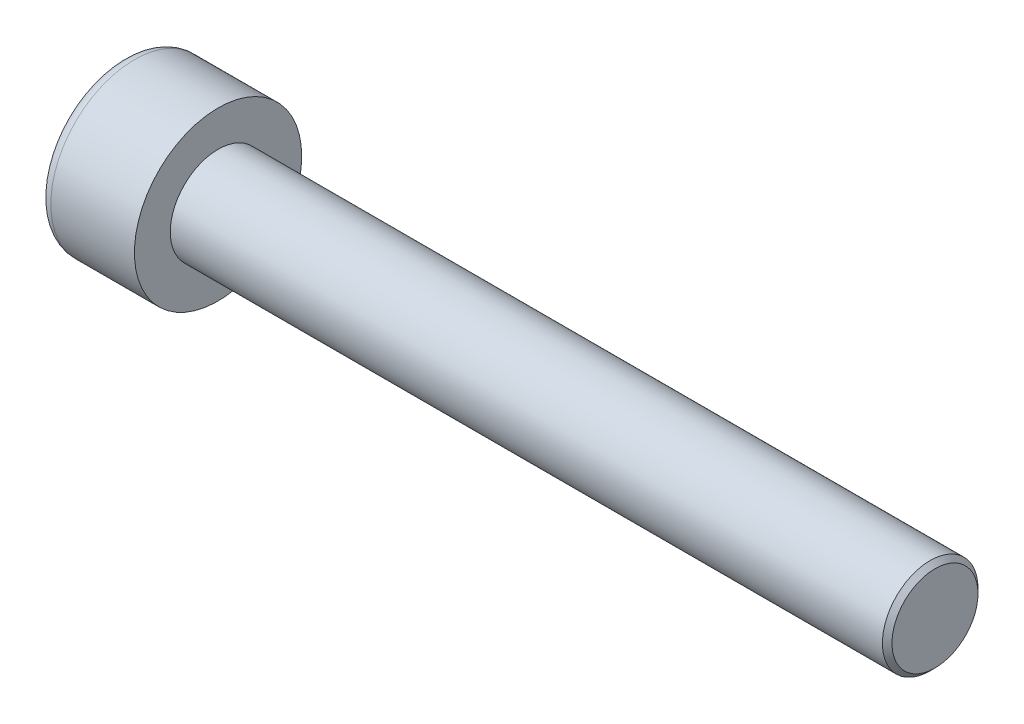
SolidWorks part; units mm, degrees
ref_plane "Front" through (0, 0, 0) normal (0, 0, 1) x (1, 0, 0)
ref_plane "Top" through (0, 0, 0) normal (0, 1, 0) x (1, 0, 0)
ref_plane "Right" through (0, 0, 0) normal (1, 0, 0) x (0, 0, -1)
other "Configuration Table"
sketch "Sketch1" plane through (0, 0, 0) normal (1, 0, 0) x (0, 0, -1)
  circle A0 centre (0, 0) radius 3.5
  dimension "dk" = 7
extrude "BaseHead" add sketch "Sketch1" along normal blind 4
sketch "Sketch2" plane through (4, 0, 0) normal (1, 0, 0) x (0, 0, -1)
  circle A0 centre (0, 0) radius 2
  dimension "d" = 4
extrude "BaseBody" add sketch "Sketch2" along normal blind 30
cosmetic thread "ThreadCosmetic1" [suppressed] parameters "b"=20, "D2"=3.242
sketch "Sketch3" plane through (0, 0, 0) normal (1, 0, 0) x (0, 0, -1)
  line L1 (1.7321, 0) -> (0.866, 1.5)
  line L2 (0.866, 1.5) -> (-0.866, 1.5)
  line L3 (-0.866, 1.5) -> (-1.7321, 0)
  line L4 (-1.7321, 0) -> (-0.866, -1.5)
  line L5 (-0.866, -1.5) -> (0.866, -1.5)
  line L6 (0.866, -1.5) -> (1.7321, 0)
  circle A0 centre (0, 0) radius 1.5 construction
  dimension "s" = 3
  dimension "e" = 3.4641
extrude "HexagonSocket" cut sketch "Sketch3" along normal blind 2
sketch "Sketch4" plane through (-4.1961, 0.75, 0) normal (0, 0, 1) x (-1, 0, 0)
  line L0 (-6.1961, 2.25) -> (-7.0622, 0.75)
  line L2 (-7.0622, 0.75) -> (-6.1961, 0.75)
  line L3 (-6.1961, 0.75) -> (-6.1961, 2.25)
  line L4 (-5.0351, 0.75) -> (0.839, 0.75) construction
  line L5 (-38.1961, 0.75) -> (-8.1961, 0.75) construction
  line L6 (-8.1961, 0.75) -> (-4.1961, 0.75) construction
  dimension "m" = 60
revolve "Cut-Revolve1" cut sketch "Sketch4" angle 360 about L4
fillet "HeadFillet" [suppressed] radius 0.2
fillet "TopFillet" radius 0.5 1 edges at (0, 0, -3.5)
chamfer "Chamfer1" distance 0.2 angle 45 1 edges at (34, 0, -2)
sketch "Sketch5" plane through (0, 0, 0) normal (0, 0, 1) x (1, 0, 0)
  line L0 (33.8, 1.6718) -> (33.9895, 2)
  line L1 (33.9895, 2) -> (33.9895, 2.379)
  line L2 (33.9895, 2.379) -> (33.6105, 2.379)
  line L3 (33.6105, 2.379) -> (33.6105, 2)
  line L4 (33.6105, 2) -> (33.8, 1.6718)
  line L5 (0, 0) -> (7.8886, 0) construction
  line L6 (33.8, -2) -> (33.8, 2) construction
  dimension "D1" = 4
  dimension "D2" = 0.379
revolve "Cut-Revolve10" [suppressed] cut sketch "Sketch5" angle 360 about L5
pattern_linear "LPattern10" [suppressed] count 44 spacing 0.4548 along (1, 0, 0)
equation "\"r1@TopFillet\" = \"d@Sketch2\" / 8"
equation "\"D1@Chamfer1\" = \"r@HeadFillet\""
equation "\"D1@Sketch5\" = \"d@Sketch2\""
equation "\"D2@Sketch5\" =  ( \"d@Sketch2\" - \"D2@ThreadCosmetic1\" )  / 2"
equation "\"D3@LPattern10\" = \"D2@Sketch5\" * 1.2"
equation "\"D1@LPattern10\" = \"b@ThreadCosmetic1\" / \"D3@LPattern10\""
